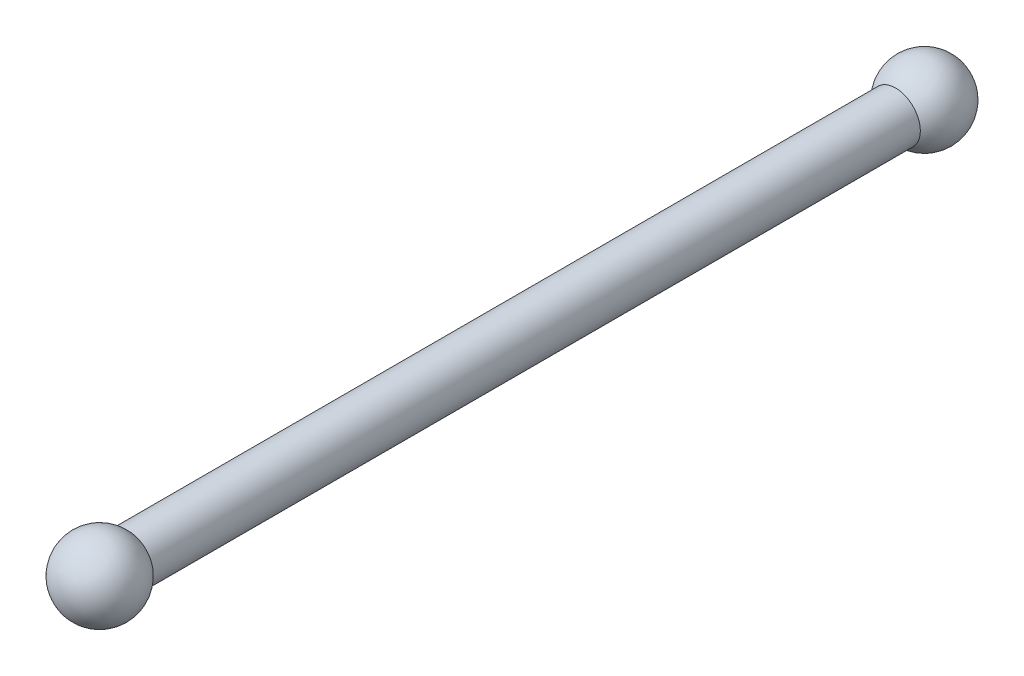
SolidWorks part; units mm, degrees
material "AISI 1020"
ref_plane "Front Plane" through (0, 0, 0) normal (0, 0, 1) x (1, 0, 0)
ref_plane "Top Plane" through (0, 0, 0) normal (0, 1, 0) x (1, 0, 0)
ref_plane "Right Plane" through (0, 0, 0) normal (1, 0, 0) x (0, 0, -1)
sketch "Sketch1" plane through (0, 0, 0) normal (0, 1, 0) x (1, 0, 0)
  line L0 (0, 292.1) -> (0, -6642.1)
  line L1 (190.5, -6128.5679) -> (190.5, -221.4321)
  line L2 (0, 292.1) -> (0, -6642.1) construction
  arc A0 (190.5, -221.4321) -> (0, 292.1) centre (0, 0) ccw
  arc A1 (0, -6642.1) -> (190.5, -6128.5679) centre (0, -6350) ccw
revolve "Revolve1" add sketch "Sketch1" angle 360 about L2
